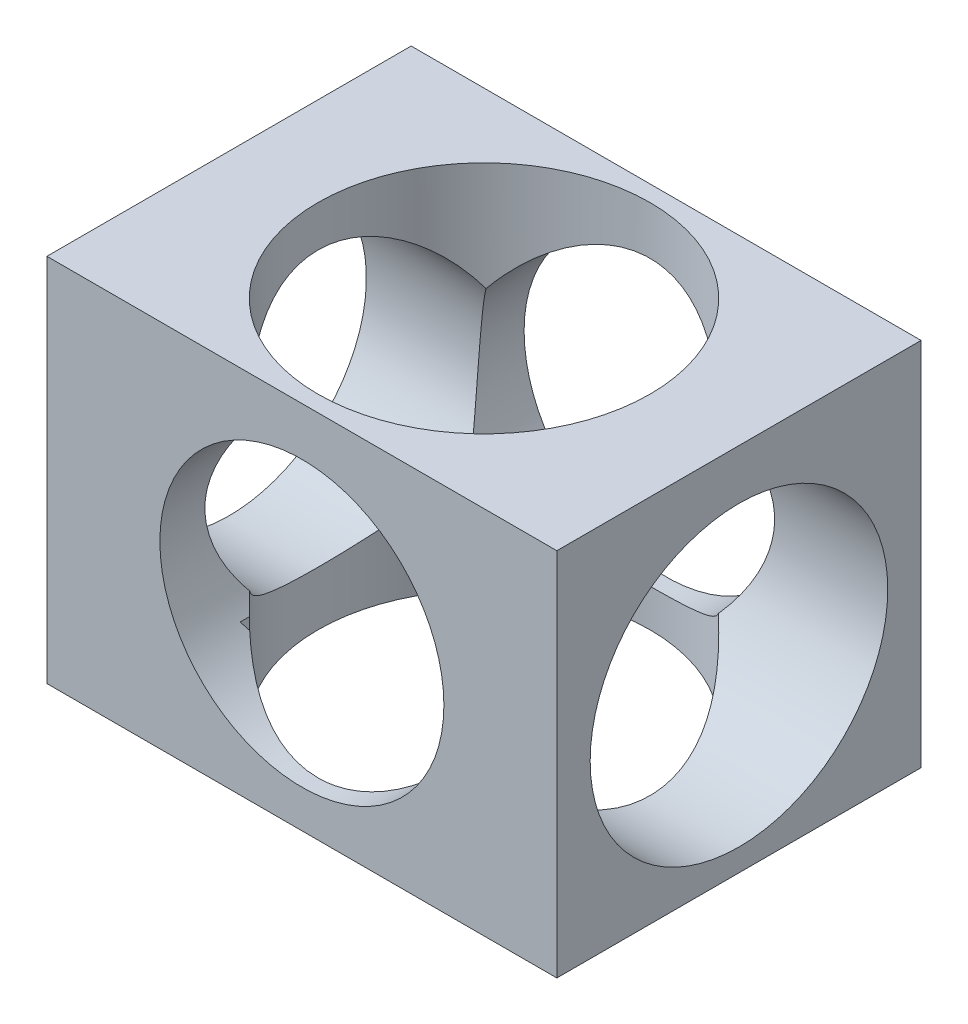
SolidWorks part; units mm, degrees
ref_plane "Front Plane" through (0, 0, 0) normal (0, 0, 1) x (1, 0, 0)
ref_plane "Top Plane" through (0, 0, 0) normal (0, 1, 0) x (1, 0, 0)
ref_plane "Right Plane" through (0, 0, 0) normal (1, 0, 0) x (0, 0, -1)
sketch "Sketch1" plane through (0, 0, 0) normal (0, 1, 0) x (1, 0, 0)
  line L1 (44.45, 31.75) -> (-44.45, 31.75)
  line L2 (44.45, 31.75) -> (44.45, -31.75)
  line L3 (44.45, -31.75) -> (-44.45, -31.75)
  line L4 (-44.45, 31.75) -> (-44.45, -31.75)
  line L5 (44.45, 31.75) -> (-44.45, -31.75) construction
  line L6 (44.45, -31.75) -> (-44.45, 31.75) construction
  point P0 (0, 0)
  dimension "D1" = 63.5
  dimension "D2" = 88.9
extrude "Boss-Extrude1" add sketch "Sketch1" along normal blind 64.516
sketch "Sketch3" plane through (-44.45, 0, 0) normal (-1, 0, 0) x (0, 0, 1)
  circle A0 centre (0, 33.4016) radius 23.9458
extrude "Cut-Extrude1" cut sketch "Sketch3" against normal blind 64.516
sketch "Sketch5" plane through (0, 0, 31.75) normal (0, 0, 1) x (1, 0, 0)
  circle A0 centre (0, 31.3395) radius 24.7566
extrude "Cut-Extrude2" cut sketch "Sketch5" against normal blind 64.516
sketch "Sketch6" plane through (44.45, 0, 0) normal (1, 0, 0) x (0, 0, -1)
  circle A0 centre (0, 29.8398) radius 25.9396
extrude "Cut-Extrude3" cut sketch "Sketch6" against normal blind 64.516
sketch "Sketch7" plane through (0, 64.516, 0) normal (0, 1, 0) x (1, 0, 0)
  circle A0 centre (0, 0) radius 28.9409
extrude "Cut-Extrude4" cut sketch "Sketch7" against normal blind 64.516
